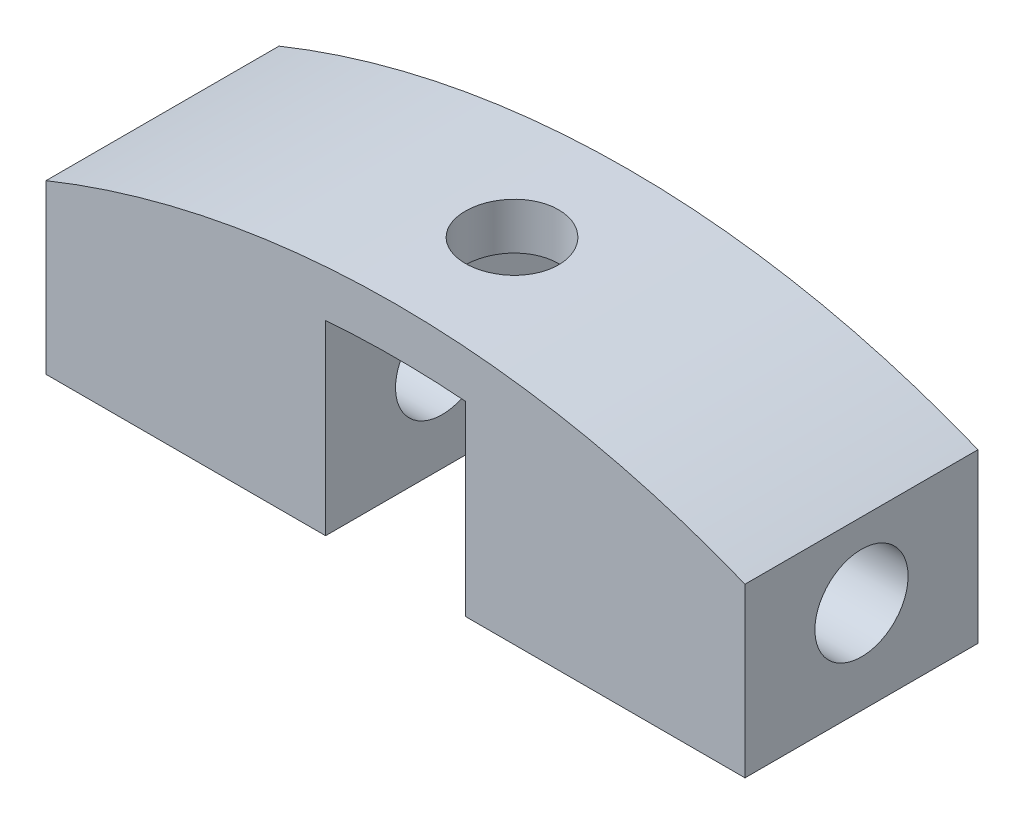
SolidWorks part; units mm, degrees
ref_plane "Front Plane" through (0, 0, 0) normal (0, 0, 1) x (1, 0, 0)
ref_plane "Top Plane" through (0, 0, 0) normal (0, 1, 0) x (1, 0, 0)
ref_plane "Right Plane" through (0, 0, 0) normal (1, 0, 0) x (0, 0, -1)
sketch "Sketch1" plane through (0, 0, 0) normal (0, 0, 1) x (1, 0, 0)
  line L0 (-15, 37.081) -> (-15, 29.8814)
  line L1 (-15, 50) -> (15, 50) construction
  line L2 (-15, 50) -> (-15, -50) construction
  line L3 (-15, -50) -> (15, -50) construction
  line L4 (15, 50) -> (15, -50) construction
  line L5 (-15, 29.8814) -> (-3, 29.8814)
  line L6 (-3, 29.8814) -> (-3, 37.8814)
  line L8 (3, 37.8814) -> (3, 29.8814)
  line L9 (3, 29.8814) -> (15, 29.8814)
  line L10 (15, 29.8814) -> (15, 37.081)
  arc A0 (-3, 37.8814) -> (3, 37.8814) centre (0, 0) cw
  circle A4 centre (0, 0) radius 30.0316 construction
  arc A5 (-15, 37.081) -> (15, 37.081) centre (0, 0) cw
  circle A6 centre (0, 0) radius 42 construction
  point P7 (0, 50)
  point P8 (-15, 0)
  dimension "D5" = 2
  dimension "D7" = 60.0632
  dimension "D8" = 40
  dimension "D1" = 84
  dimension "D2" = 30
  dimension "D3" = 100
  dimension "D4" = 8
  dimension "D6" = 6
extrude "Boss-Extrude1" add sketch "Sketch1" against normal blind 10 contours A5 L0 L5 L6 A0 L8 L9 L10
sketch "Sketch4" plane through (-3, 0, 0) normal (1, 0, 0) x (0, 0, -1)
  line L0 (0, 33.8814) -> (10, 33.8814) construction
  line L4 (0, 37.8814) -> (0, 29.8814)
  line L5 (0, 29.8814) -> (10, 29.8814)
  line L6 (10, 29.8814) -> (10, 37.8814)
  line L7 (10, 37.8814) -> (0, 37.8814)
  line L8 (0, 37.8814) -> (0, 29.8814)
  line L9 (0, 29.8814) -> (10, 29.8814)
  line L10 (10, 29.8814) -> (10, 37.8814)
  line L11 (10, 37.8814) -> (0, 37.8814)
  circle A0 centre (5, 33.8814) radius 2
  dimension "D2" = 4
  dimension "D1" = 0
extrude "Cut-Extrude2" cut sketch "Sketch4" against normal through all both and the other way through all contours A0 L0 | L0 A0
sketch "Sketch5" plane through (0, 0, 0) normal (0, 1, 0) x (1, 0, 0)
  line L0 (-15, 5) -> (15, 5) construction
  line L1 (-15, 10) -> (-15, 0) construction
  line L2 (15, 10) -> (15, 0) construction
  circle A0 centre (0, 5) radius 2
  dimension "D1" = 4
extrude "Cut-Extrude3" cut sketch "Sketch5" along normal through all
